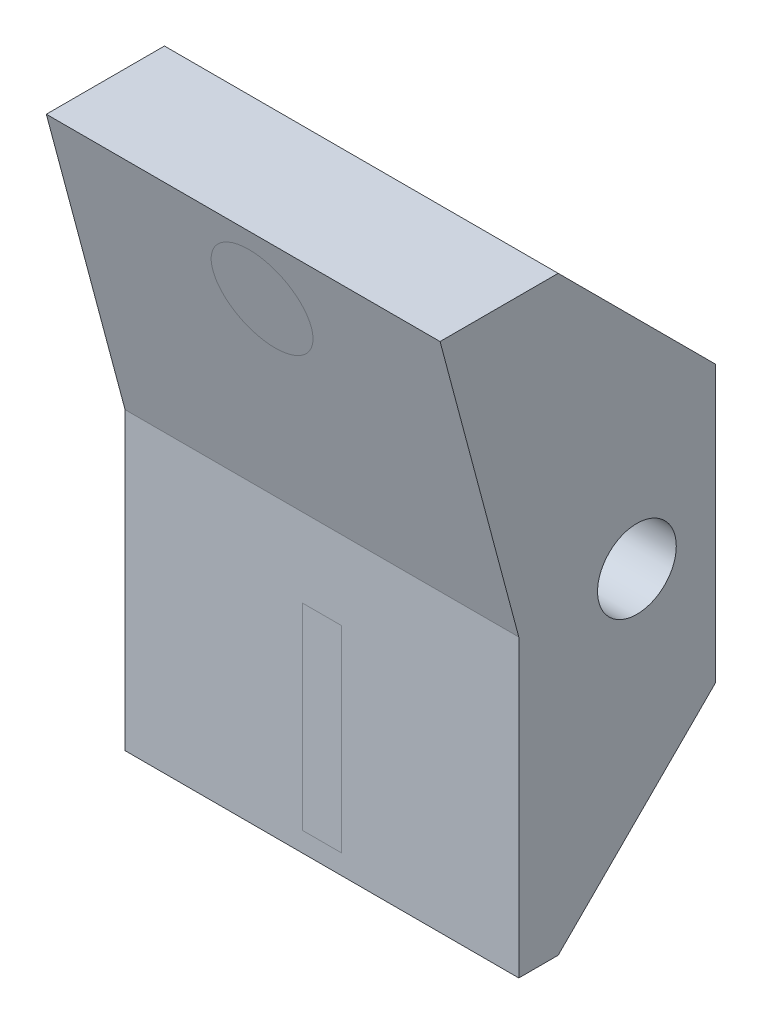
SolidWorks part; units mm, degrees
ref_plane "Front Plane" through (0, 0, 0) normal (0, 0, 1) x (1, 0, 0)
ref_plane "Top Plane" through (0, 0, 0) normal (0, 1, 0) x (1, 0, 0)
ref_plane "Right Plane" through (0, 0, 0) normal (1, 0, 0) x (0, 0, -1)
sketch "Sketch1" plane through (0, 0, 0) normal (0, 0, 1) x (1, 0, 0)
  line L1 (63.5, -95.25) -> (-63.5, -95.25)
  line L2 (63.5, -95.25) -> (63.5, 95.25)
  line L3 (63.5, 95.25) -> (-63.5, 95.25)
  line L4 (-63.5, -95.25) -> (-63.5, 95.25)
  line L5 (63.5, -95.25) -> (-63.5, 95.25) construction
  line L6 (63.5, 95.25) -> (-63.5, -95.25) construction
  point P0 (0, 0)
extrude "Boss-Extrude1" add sketch "Sketch1" along normal blind 63.5
sketch "Sketch2" plane through (63.5, 0, 0) normal (1, 0, 0) x (0, 0, -1)
  line L0 (-63.5, -95.25) -> (0, -95.25) construction
  line L1 (0, -95.25) -> (0, 95.25) construction
  point P0 (-50.8, -95.25)
  point P1 (0, -44.45)
  dimension "D1" = 50.8
  dimension "D2" = 50.8
sketch "Sketch3" plane through (-63.5, 0, 0) normal (-1, 0, 0) x (0, 0, 1)
  point P0 (50.8, -95.25)
ref_plane "Plane1" through (0, -22.225, -22.225) normal (0, 0.7071, 0.7071) x (1, 0, 0)
sketch "Sketch4" plane through (0, -22.225, -22.225) normal (0, 0.7071, 0.7071) x (1, 0, 0)
  line L1 (-63.5, -103.2729) -> (63.5, -103.2729)
  line L2 (-63.5, -103.2729) -> (-63.5, -31.4309)
  line L3 (-63.5, -31.4309) -> (63.5, -31.4309)
  line L4 (63.5, -103.2729) -> (63.5, -31.4309)
extrude "Cut-Extrude1" cut sketch "Sketch4" against normal blind 63.5
sketch "Sketch5" plane through (63.5, 0, 0) normal (1, 0, 0) x (0, 0, -1)
  circle A0 centre (-25.4, 0) radius 12.7
  dimension "D1" = 25.4
  dimension "D2" = 25.4
extrude "Cut-Extrude2" cut sketch "Sketch5" against normal blind 137.16
mirror "Mirror1" about plane through (0, 0, 0) normal (0, 1, 0) of "Cut-Extrude1"
sketch "Sketch7" plane through (63.5, 0, 0) normal (1, 0, 0) x (0, 0, -1)
  line L0 (-63.5, 95.25) -> (-88.9, 95.25)
  line L1 (-63.5, 95.25) -> (-63.5, 0)
  line L3 (-63.5, 0) -> (-88.9, 95.25)
  line L4 (-63.5, -95.25) -> (-63.5, 95.25) construction
  point P3 (0, 0)
  point P5 (0, 0)
  point P11 (-63.5, 89.6631)
  point P12 (0, 0)
  dimension "D2" = 25.4
extrude "Boss-Extrude2" add sketch "Sketch7" against normal blind 127
sketch "Sketch6" plane through (0, 0, 63.5) normal (0, 0, 1) x (1, 0, 0)
  line L1 (-6.35, -25.4) -> (6.35, -25.4)
  line L2 (-6.35, -25.4) -> (-6.35, -88.9)
  line L3 (-6.35, -88.9) -> (6.35, -88.9)
  line L4 (6.35, -25.4) -> (6.35, -88.9)
  circle A0 centre (0, 72.39) radius 15.875
  point P6 (6.35, -57.15)
  point P7 (0, -25.4)
  dimension "D1" = 72.39
  dimension "D5" = 31.75
  dimension "D2" = 57.15
  dimension "D3" = 63.5
  dimension "D4" = 12.7
split line "Split Line2"
